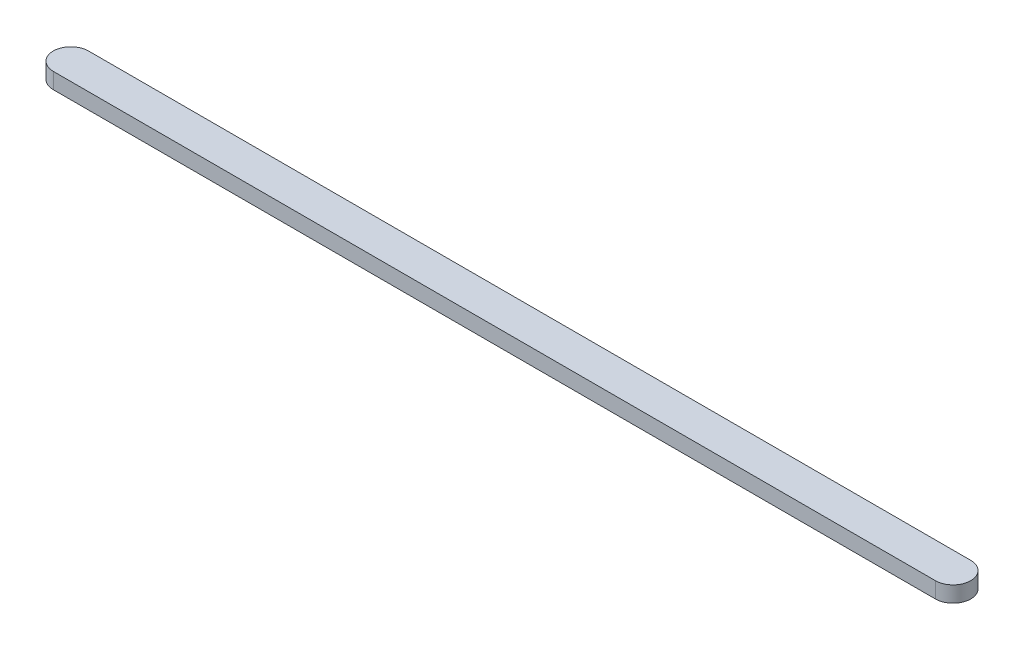
SolidWorks part; units mm, degrees
material "Perspex (TM) GS Acrylic Cast Sheet"
ref_plane "Front Plane" through (0, 0, 0) normal (0, 0, 1) x (1, 0, 0)
ref_plane "Top Plane" through (0, 0, 0) normal (0, 1, 0) x (1, 0, 0)
ref_plane "Right Plane" through (0, 0, 0) normal (1, 0, 0) x (0, 0, -1)
sketch "Sketch1" plane through (0, 0, 0) normal (0, 1, 0) x (1, 0, 0)
  line L0 (-100, 0) -> (150, 0) construction
  line L1 (-100, 5) -> (150, 5)
  line L2 (-100, -5) -> (150, -5)
  arc A0 (-100, 5) -> (-100, -5) centre (-100, 0) ccw
  arc A1 (150, -5) -> (150, 5) centre (150, 0) ccw
  point P2 (25, 0)
  dimension "D2" = 5
  dimension "D1" = 250
extrude "Boss-Extrude1" add sketch "Sketch1" along normal blind 4.5
sketch "Sketch2" plane through (0, 4.5, 0) normal (0, 1, 0) x (1, 0, 0)
  circle A0 centre (150, 0) radius 3.125
  circle A2 centre (-100, 0) radius 3.125
  dimension "D1" = 6.25
